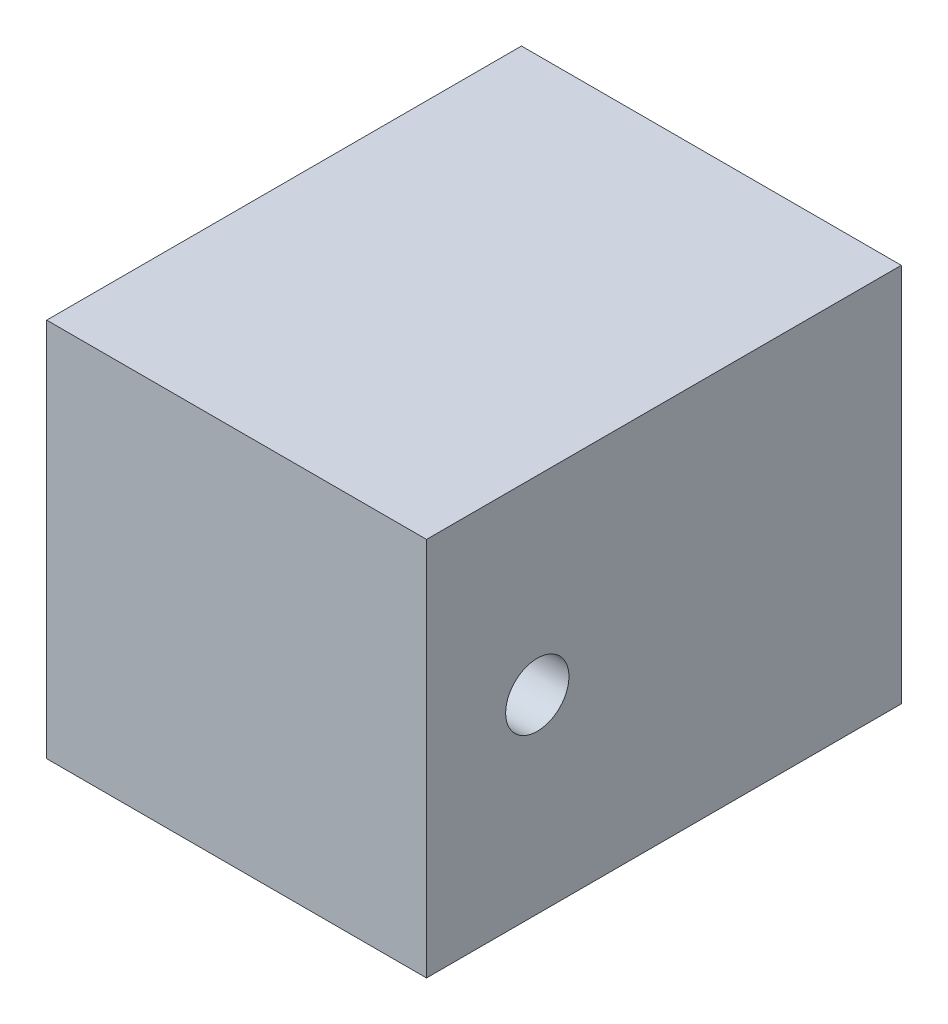
SolidWorks part; units mm, degrees
ref_plane "前视基准面" through (0, 0, 0) normal (0, 0, 1) x (1, 0, 0)
ref_plane "上视基准面" through (0, 0, 0) normal (0, 1, 0) x (1, 0, 0)
ref_plane "右视基准面" through (0, 0, 0) normal (1, 0, 0) x (0, 0, -1)
sketch "草图1" plane through (0, 0, 0) normal (0, 0, 1) x (1, 0, 0)
  line L1 (0, 0) -> (12, 0)
  line L2 (0, 0) -> (0, 12)
  line L3 (0, 12) -> (12, 12)
  line L4 (12, 0) -> (12, 12)
  line L5 (1, 1) -> (11, 1)
  line L6 (1, 1) -> (1, 11)
  line L7 (1, 11) -> (11, 11)
  line L8 (11, 1) -> (11, 11)
  point P5 (1, 1)
extrude "凸台-拉伸1" add sketch "草图1" along normal blind 10
sketch "草图2" plane through (0, 0, 10) normal (0, 0, 1) x (1, 0, 0)
  line L1 (0, 12) -> (12, 12)
  line L2 (0, 12) -> (0, 0)
  line L3 (0, 0) -> (12, 0)
  line L4 (12, 12) -> (12, 0)
extrude "凸台-拉伸2" add sketch "草图2" along normal blind 5
sketch "草图3" plane through (0, 0, 0) normal (-1, 0, 0) x (0, 0, 1)
  circle A0 centre (11.5, 6) radius 1
  point P0 (11.5, 6)
extrude "切除-拉伸1" cut sketch "草图3" against normal blind 12
